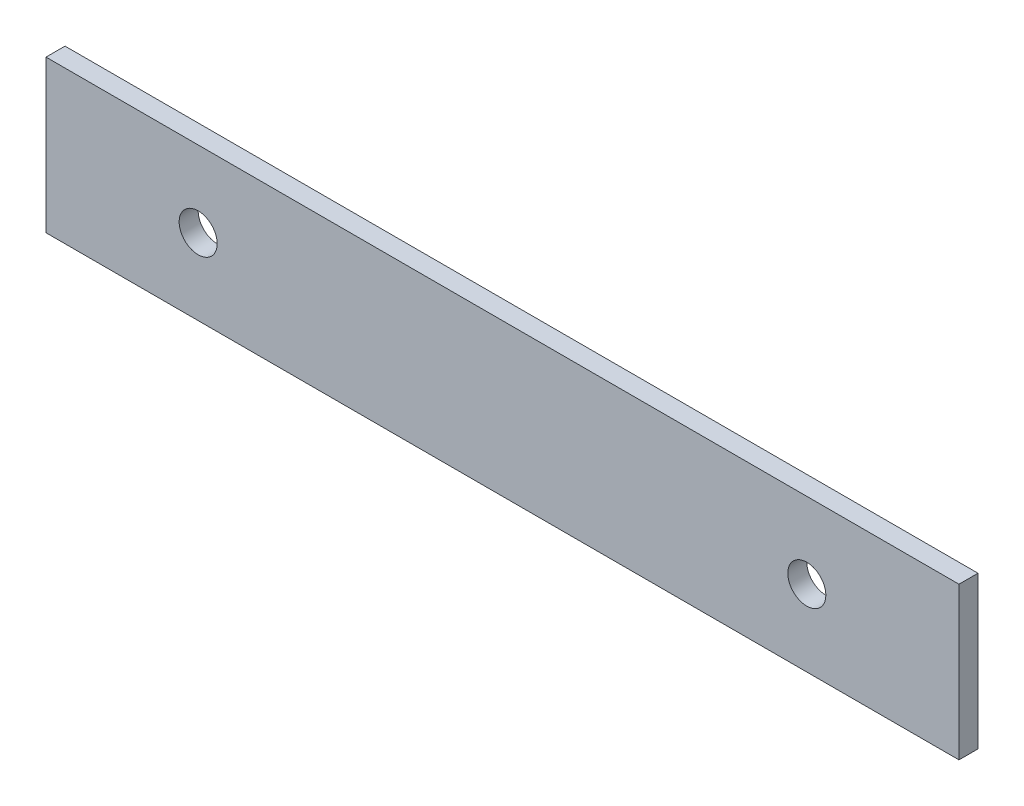
SolidWorks part; units mm, degrees
ref_plane "Front Plane" through (0, 0, 0) normal (0, 0, 1) x (1, 0, 0)
ref_plane "Top Plane" through (0, 0, 0) normal (0, 1, 0) x (1, 0, 0)
ref_plane "Right Plane" through (0, 0, 0) normal (1, 0, 0) x (0, 0, -1)
sketch "Sketch1" plane through (0, 0, 0) normal (0, 0, 1) x (1, 0, 0)
  line L0 (0, 0) -> (50.8, 0) construction
  line L1 (76.2, -12.7) -> (-76.2, -12.7)
  line L2 (76.2, -12.7) -> (76.2, 12.7)
  line L3 (76.2, 12.7) -> (-76.2, 12.7)
  line L4 (-76.2, -12.7) -> (-76.2, 12.7)
  line L5 (76.2, -12.7) -> (-76.2, 12.7) construction
  line L6 (76.2, 12.7) -> (-76.2, -12.7) construction
  line L7 (0, 12.7) -> (0, -12.7) construction
  circle A0 centre (50.8, 0) radius 3.175
  circle A1 centre (-50.8, 0) radius 3.175
  point P0 (0, 0)
  dimension "D3" = 6.35
  dimension "D1" = 152.4
  dimension "D2" = 25.4
  dimension "D4" = 50.8
extrude "Boss-Extrude1" add sketch "Sketch1" along normal blind 3.175
